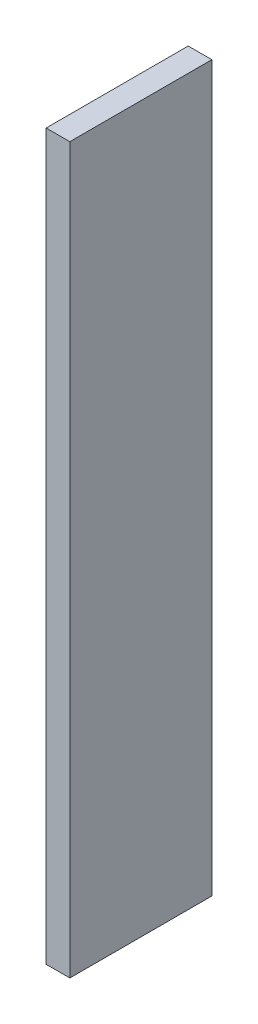
SolidWorks part; units mm, degrees
ref_plane "Спереди" through (0, 0, 0) normal (0, 0, 1) x (1, 0, 0)
ref_plane "Сверху" through (0, 0, 0) normal (0, 1, 0) x (1, 0, 0)
ref_plane "Справа" through (0, 0, 0) normal (1, 0, 0) x (0, 0, -1)
sketch "Эскиз1" plane through (0, 0, 0) normal (0, 1, 0) x (1, 0, 0)
  line L1 (0, 0) -> (5, 0)
  line L2 (0, 0) -> (0, -30)
  line L3 (0, -30) -> (5, -30)
  line L4 (5, 0) -> (5, -30)
  dimension "D1" = 5
  dimension "D2" = 30
extrude "Бобышка-Вытянуть1" add sketch "Эскиз1" along normal blind 153
